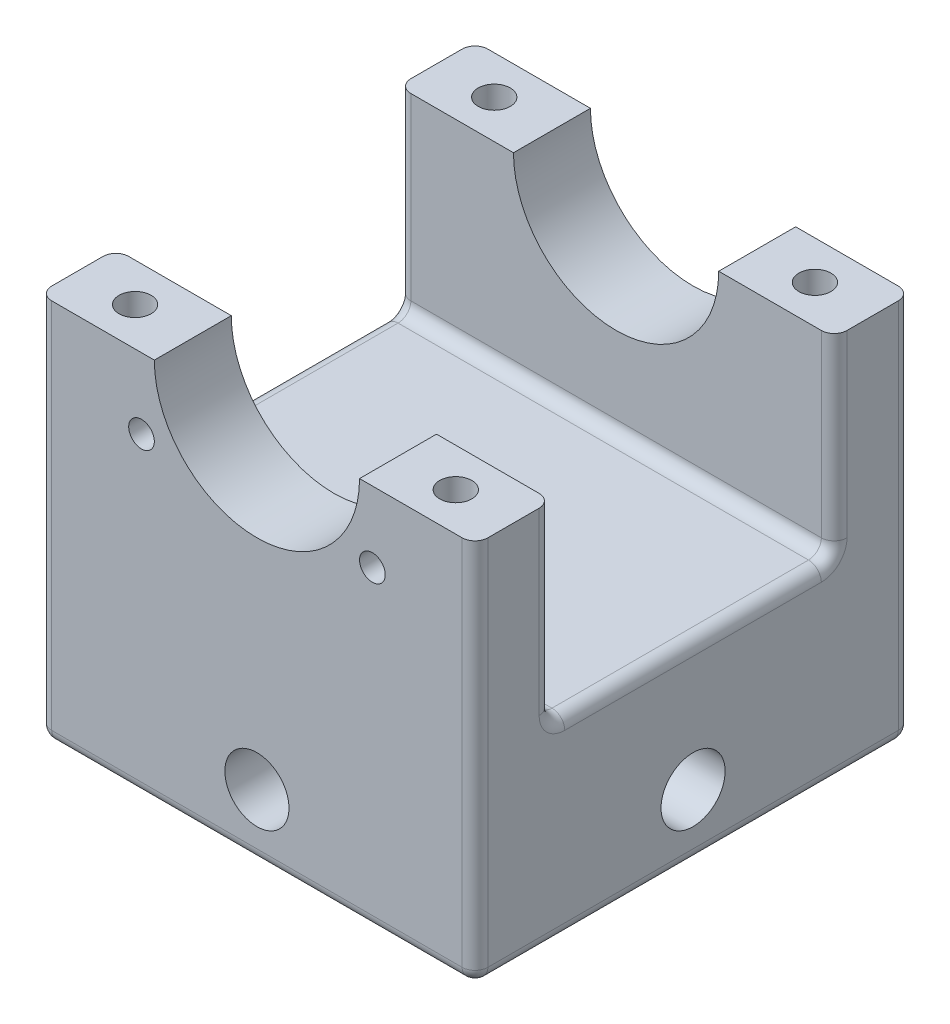
SolidWorks part; units mm, degrees
ref_plane "Front Plane" through (0, 0, 0) normal (0, 0, 1) x (1, 0, 0)
ref_plane "Top Plane" through (0, 0, 0) normal (0, 1, 0) x (1, 0, 0)
ref_plane "Right Plane" through (0, 0, 0) normal (1, 0, 0) x (0, 0, -1)
sketch "Sketch1" plane through (0, 0, 0) normal (0, 1, 0) x (1, 0, 0)
  line L1 (-17, 17) -> (17, 17)
  line L2 (-17, 17) -> (-17, -17)
  line L3 (-17, -17) -> (17, -17)
  line L4 (17, 17) -> (17, -17)
  line L5 (-17, 17) -> (17, -17) construction
  line L6 (-17, -17) -> (17, 17) construction
  point P0 (0, 0)
  dimension "D1" = 34
  dimension "D2" = 34
extrude "Boss-Extrude1" add sketch "Sketch1" along normal blind 15
sketch "Sketch2" plane through (0, 0, 0) normal (0, -1, 0) x (1, 0, 0)
  line L1 (-10.1, -10.1) -> (10.1, -10.1)
  line L2 (-10.1, -10.1) -> (-10.1, 10.1)
  line L3 (-10.1, 10.1) -> (10.1, 10.1)
  line L4 (10.1, -10.1) -> (10.1, 10.1)
  line L5 (-10.1, -10.1) -> (10.1, 10.1) construction
  line L6 (-10.1, 10.1) -> (10.1, -10.1) construction
  point P0 (0, 0)
  dimension "D1" = 20.2
  dimension "D2" = 20.2
extrude "Cut-Extrude1" cut sketch "Sketch2" against normal blind 10
sketch "Sketch4" plane through (0, 0, 17) normal (0, 0, 1) x (1, 0, 0)
  line L0 (-17, 30) -> (-17, 15)
  line L1 (-17, 15) -> (17, 15)
  line L2 (17, 15) -> (17, 30)
  line L3 (17, 30) -> (-17, 30)
  dimension "D1" = 15
extrude "Boss-Extrude2" add sketch "Sketch4" against normal blind 6
sketch "Sketch7" plane through (0, 0, 17) normal (0, 0, 1) x (1, 0, 0)
  line L0 (17, 30) -> (-17, 30) construction
  circle A0 centre (0, 30) radius 8
  dimension "D1" = 16
extrude "Cut-Extrude4" cut sketch "Sketch7" against normal through all
sketch "Sketch17" plane through (0, 30, 0) normal (0, 1, 0) x (1, 0, 0)
  line L0 (-17, -14) -> (-8, -14) construction
  line L1 (-17, -11) -> (-17, -17) construction
  line L2 (-8, -11) -> (-8, -17) construction
  line L3 (8, -14) -> (17, -14) construction
  line L4 (8, -17) -> (8, -11) construction
  line L5 (17, -11) -> (17, -17) construction
  circle A0 centre (-12.5, -14) radius 1.25
  circle A1 centre (12.5, -14) radius 1.25
  dimension "D1" = 2.5
  dimension "D2" = 2.5
extrude "Cut-Extrude10" cut sketch "Sketch17" against normal blind 10
mirror "Mirror1" about plane through (0, 0, 0) normal (0, 0, 1) of "Cut-Extrude10", "Boss-Extrude2", "Cut-Extrude4"
sketch "Sketch15" plane through (0, 0, -17) normal (0, 0, -1) x (-1, 0, 0)
  line L0 (17, 0) -> (-17, 0) construction
  circle A0 centre (0, 5) radius 2.5
  dimension "D1" = 5
  dimension "D2" = 5
extrude "Cut-Extrude8" cut sketch "Sketch15" against normal through all
sketch "Sketch16" plane through (17, 0, 0) normal (1, 0, 0) x (0, 0, -1)
  circle A0 centre (0, 5) radius 2.5
  dimension "D1" = 5
  dimension "D2" = 5
extrude "Cut-Extrude9" cut sketch "Sketch16" against normal through all
fillet "Fillet2" radius 1 16 edges at (17, 15, -17) (-17, 15, 17) (17, 15, 17) (-17, 0, 0) (0, 0, -17) (17, 0, 0) (0, 0, 17) (-17, 15, -17) (-17, 22.5, -11) (17, 22.5, -11) (0, 15, -11)
sketch "Sketch19" plane through (0, 0, 17) normal (0, 0, 1) x (1, 0, 0)
  circle A0 centre (-9, 24.5) radius 1
  arc A1 (-8, 30) -> (8, 30) centre (0, 30) ccw construction
  dimension "D1" = 2
  dimension "D2" = 9
  dimension "D3" = 5.5
extrude "Cut-Extrude12" cut sketch "Sketch19" against normal blind 3
mirror "Mirror2" about plane through (0, 0, 0) normal (1, 0, 0) of "Cut-Extrude12"
